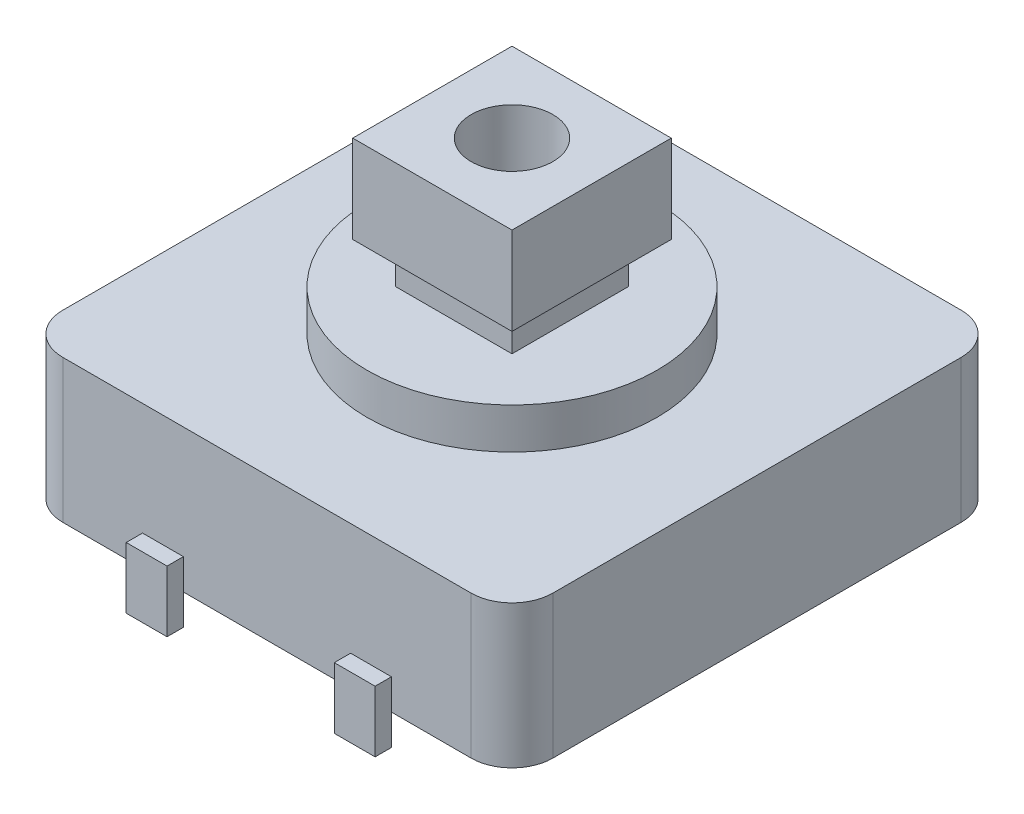
SolidWorks part; units mm, degrees
ref_plane "Front Plane" through (0, 0, 0) normal (0, 0, 1) x (1, 0, 0)
ref_plane "Top Plane" through (0, 0, 0) normal (0, 1, 0) x (1, 0, 0)
ref_plane "Right Plane" through (0, 0, 0) normal (1, 0, 0) x (0, 0, -1)
sketch "Sketch1" plane through (0, 0, 0) normal (0, 1, 0) x (1, 0, 0)
  line L1 (-5, -6) -> (5, -6)
  line L2 (-6, -5) -> (-6, 5)
  line L3 (-5, 6) -> (5, 6)
  line L4 (6, -5) -> (6, 5)
  line L5 (-6, -6) -> (6, 6) construction
  line L6 (-6, 6) -> (6, -6) construction
  arc A0 (5, 6) -> (6, 5) centre (5, 5) cw
  arc A1 (5, -6) -> (6, -5) centre (5, -5) ccw
  arc A2 (-5, -6) -> (-6, -5) centre (-5, -5) cw
  arc A3 (-6, 5) -> (-5, 6) centre (-5, 5) cw
  point P0 (0, 0)
  dimension "D3" = 1
  dimension "D1" = 12
  dimension "D2" = 12
extrude "Boss-Extrude1" add sketch "Sketch1" along normal blind 3.5
sketch "Sketch2" plane through (0, 3.5, 0) normal (0, 1, 0) x (1, 0, 0)
  circle A0 centre (0, 0) radius 3.55
  dimension "D1" = 7.1
extrude "Boss-Extrude2" add sketch "Sketch2" along normal blind 1
sketch "Sketch3" plane through (0, 4.5, 0) normal (0, 1, 0) x (1, 0, 0)
  line L1 (-1.425, -1.425) -> (1.425, -1.425)
  line L2 (-1.425, -1.425) -> (-1.425, 1.425)
  line L3 (-1.425, 1.425) -> (1.425, 1.425)
  line L4 (1.425, -1.425) -> (1.425, 1.425)
  line L5 (-1.425, -1.425) -> (1.425, 1.425) construction
  line L6 (-1.425, 1.425) -> (1.425, -1.425) construction
  point P0 (0, 0)
  dimension "D1" = 2.85
  dimension "D2" = 2.85
extrude "Boss-Extrude3" add sketch "Sketch3" along normal blind 1
sketch "Sketch4" plane through (0, 5.5, 0) normal (0, 1, 0) x (1, 0, 0)
  line L1 (-1.95, -1.95) -> (1.95, -1.95)
  line L2 (-1.95, -1.95) -> (-1.95, 1.95)
  line L3 (-1.95, 1.95) -> (1.95, 1.95)
  line L4 (1.95, -1.95) -> (1.95, 1.95)
  line L5 (-1.95, -1.95) -> (1.95, 1.95) construction
  line L6 (-1.95, 1.95) -> (1.95, -1.95) construction
  circle A0 centre (0, 0) radius 1
  point P0 (0, 0)
  dimension "D3" = 2
  dimension "D1" = 3.9
  dimension "D2" = 3.9
extrude "Boss-Extrude4" add sketch "Sketch4" along normal blind 2.15
sketch "Sketch5" plane through (0, 0, 6) normal (0, 0, 1) x (1, 0, 0)
  line L0 (-5, 0) -> (5, 0) construction
  line L1 (-3.0477, -0.75) -> (-2.0477, -0.75)
  line L2 (-3.0477, -0.75) -> (-3.0477, 0.75)
  line L3 (-3.0477, 0.75) -> (-2.0477, 0.75)
  line L4 (-2.0477, -0.75) -> (-2.0477, 0.75)
  line L5 (-3.0477, -0.75) -> (-2.0477, 0.75) construction
  line L6 (-3.0477, 0.75) -> (-2.0477, -0.75) construction
  line L7 (0, 0) -> (0, 1.3024) construction
  line L8 (3.0477, 0.75) -> (2.0477, -0.75) construction
  line L9 (3.0477, -0.75) -> (2.0477, 0.75) construction
  line L10 (2.0477, -0.75) -> (2.0477, 0.75)
  line L11 (3.0477, -0.75) -> (3.0477, 0.75)
  line L12 (3.0477, -0.75) -> (2.0477, -0.75)
  line L13 (3.0477, 0.75) -> (2.0477, 0.75)
  point P0 (-2.5477, 0)
  point P14 (2.5477, 0)
  dimension "D1" = 1
  dimension "D2" = 1.5
extrude "Boss-Extrude5" add sketch "Sketch5" along normal blind 0.4
mirror "Mirror1" about plane through (0, 0, 0) normal (0, 0, 1) of "Boss-Extrude5"
